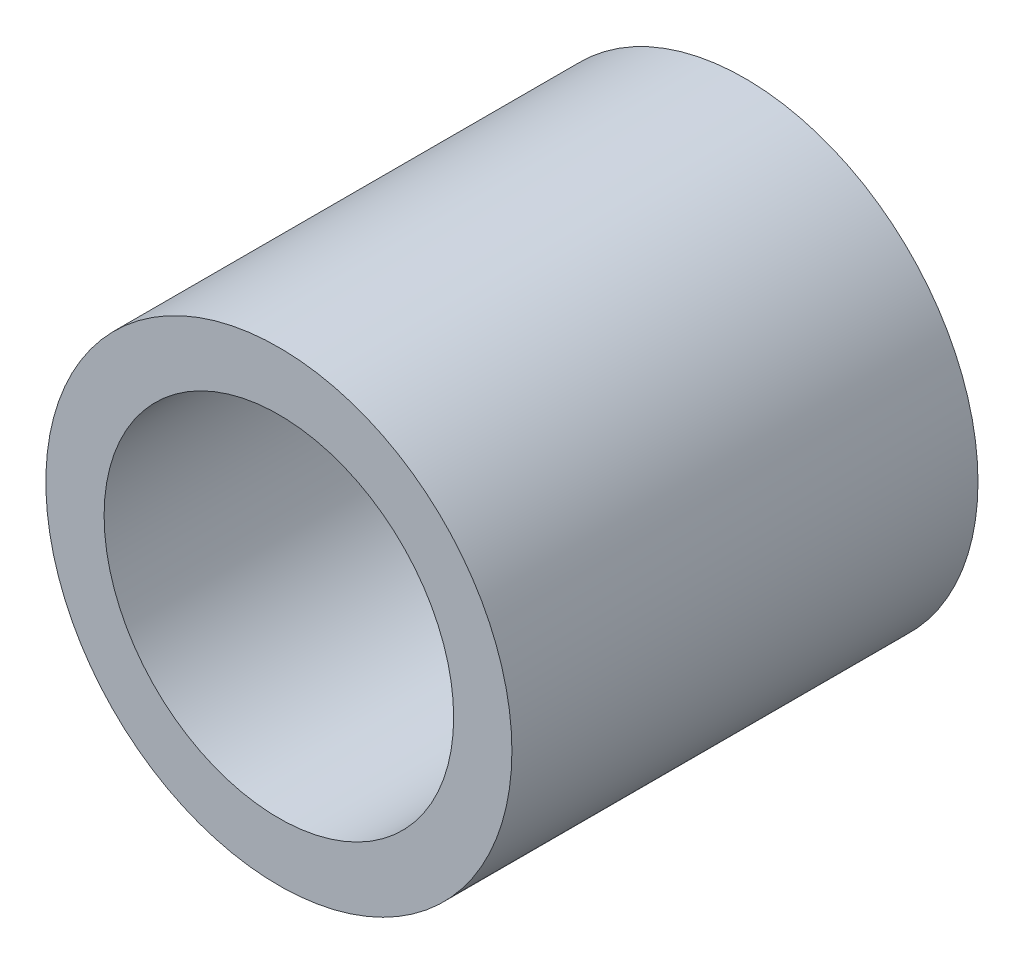
SolidWorks part; units mm, degrees
ref_plane "Front Plane" through (0, 0, 0) normal (0, 0, 1) x (1, 0, 0)
ref_plane "Top Plane" through (0, 0, 0) normal (0, 1, 0) x (1, 0, 0)
ref_plane "Right Plane" through (0, 0, 0) normal (1, 0, 0) x (0, 0, -1)
sketch "Sketch1" plane through (0, 0, 0) normal (0, 0, 1) x (1, 0, 0)
  circle A0 centre (0, 0) radius 19.05
  circle A1 centre (0, 0) radius 25.4
  dimension "D1" = 38.1
  dimension "D2" = 50.8
extrude "Boss-Extrude1" add sketch "Sketch1" along normal blind 50.8
